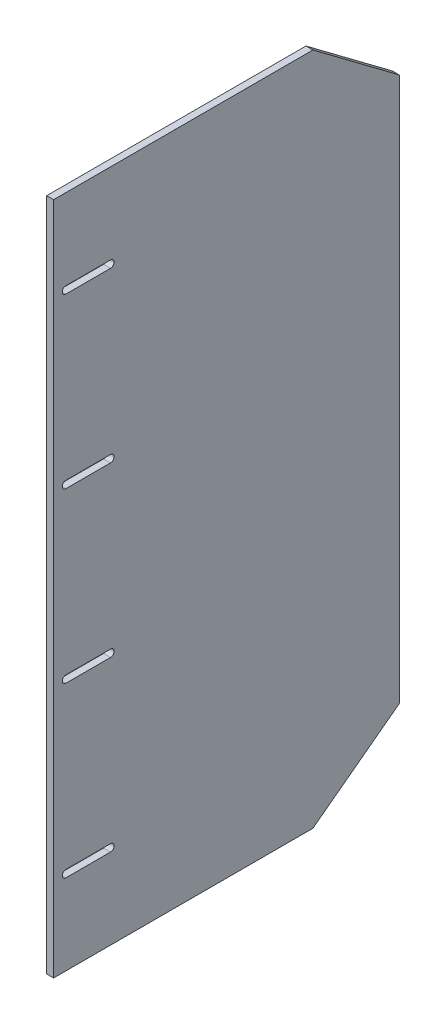
SolidWorks part; units mm, degrees
ref_plane "Front Plane" through (0, 0, 0) normal (1, 0, 0) x (0, 1, 0)
ref_plane "Top Plane" through (0, 0, 0) normal (0, 0, 1) x (0, 1, 0)
ref_plane "Right Plane" through (0, 0, 0) normal (0, 1, 0) x (-1, 0, 0)
sketch "Sketch1" plane through (0, 0, 0) normal (1, 0, 0) x (0, 1, 0)
  line L1 (390, 0) -> (390, 150)
  line L2 (390, 150) -> (0, 150)
  line L3 (0, 150) -> (0, 0)
  line L4 (0, 0) -> (37.5, -50)
  line L5 (37.5, -50) -> (352.5, -50)
  line L6 (352.5, -50) -> (390, 0)
  line L7 (48.75, 142.9) -> (48.75, 117.1) construction
  line L8 (46.65, 142.9) -> (46.65, 117.1)
  line L9 (50.85, 142.9) -> (50.85, 117.1)
  line L10 (195, 150) -> (195, 101.8617) construction
  line L11 (97.5, 150) -> (97.5, 111.5799) construction
  line L12 (146.25, 142.9) -> (146.25, 117.1) construction
  line L13 (148.35, 142.9) -> (148.35, 117.1)
  line L14 (144.15, 142.9) -> (144.15, 117.1)
  line L15 (243.75, 142.9) -> (243.75, 117.1) construction
  line L16 (241.65, 142.9) -> (241.65, 117.1)
  line L17 (245.85, 142.9) -> (245.85, 117.1)
  line L18 (341.25, 142.9) -> (341.25, 117.1) construction
  line L19 (343.35, 142.9) -> (343.35, 117.1)
  line L20 (339.15, 142.9) -> (339.15, 117.1)
  arc A0 (46.65, 142.9) -> (50.85, 142.9) centre (48.75, 142.9) cw
  arc A1 (50.85, 117.1) -> (46.65, 117.1) centre (48.75, 117.1) cw
  arc A2 (148.35, 142.9) -> (144.15, 142.9) centre (146.25, 142.9) ccw
  arc A3 (144.15, 117.1) -> (148.35, 117.1) centre (146.25, 117.1) ccw
  arc A4 (241.65, 142.9) -> (245.85, 142.9) centre (243.75, 142.9) cw
  arc A5 (245.85, 117.1) -> (241.65, 117.1) centre (243.75, 117.1) cw
  arc A6 (343.35, 142.9) -> (339.15, 142.9) centre (341.25, 142.9) ccw
  arc A7 (339.15, 117.1) -> (343.35, 117.1) centre (341.25, 117.1) ccw
  point P7 (195, -50)
  point P8 (195, 150)
  point P11 (48.75, 130)
  point P20 (0, 0)
  point P21 (44.1902, 130)
  point P24 (146.25, 130)
  point P31 (243.75, 130)
  point P38 (341.25, 130)
  dimension "D1" = 390
  dimension "D2" = 150
  dimension "D3" = 50
  dimension "D4" = 315
  dimension "D5" = 30
  dimension "D6" = 4.2
  dimension "D7" = 5
  dimension "D8" = 97.5
  dimension "D9" = 48.75
extrude "Boss-Extrude1" add sketch "Sketch1" along normal blind 4 contours L5 L6 L1 L2 L3 L4 A7 L20 A6 L19 A3 L14 A2 L13 L9 A1 L8 A0 L17 A5 L16 A4
equation "\"D8@Sketch1\"=\"D1@Sketch1\"/4"
equation "\"D9@Sketch1\"=\"D8@Sketch1\"/2"
